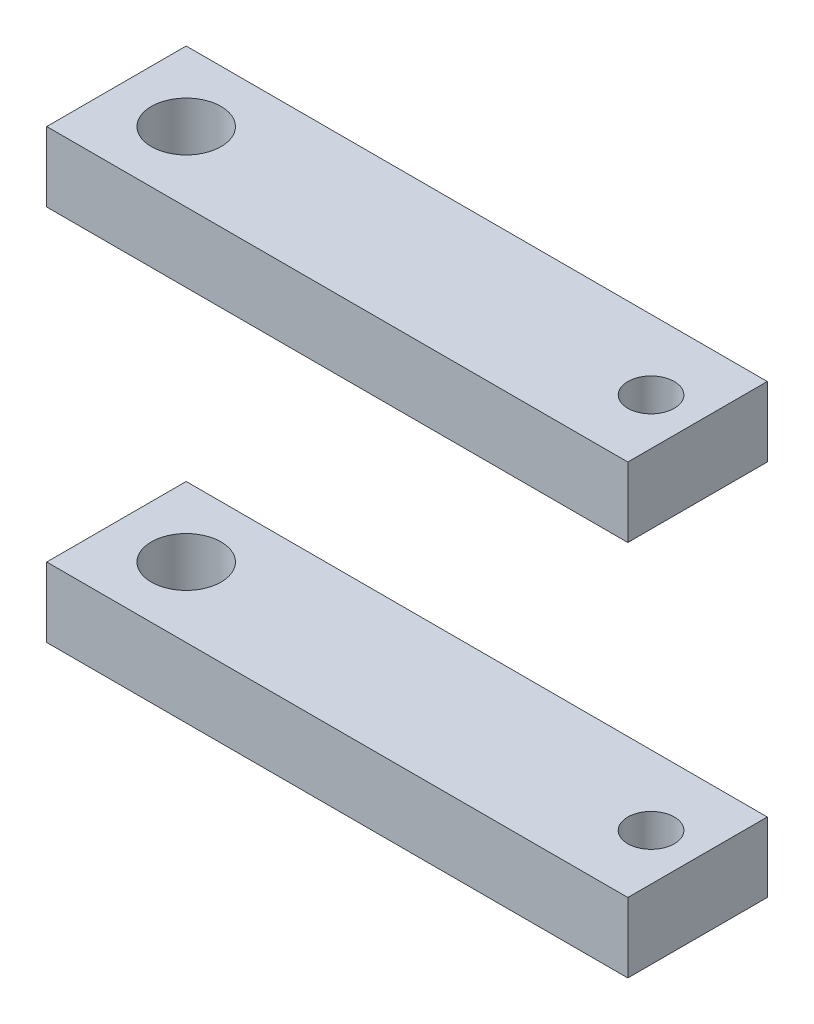
SolidWorks part; units mm, degrees
ref_plane "Ön Düzlem" through (0, 0, 0) normal (0, 0, 1) x (1, 0, 0)
ref_plane "Üst Düzlem" through (0, 0, 0) normal (0, 1, 0) x (1, 0, 0)
ref_plane "Sağ Düzlem" through (0, 0, 0) normal (1, 0, 0) x (0, 0, -1)
sketch "Çizim1" plane through (0, 0, 0) normal (0, 0, 1) x (1, 0, 0)
  line L1 (-12.5276, -4.1892) -> (-62.5276, -4.1892)
  line L2 (-12.5276, -4.1892) -> (-12.5276, -10.1892)
  line L3 (-12.5276, -10.1892) -> (-62.5276, -10.1892)
  line L4 (-62.5276, -4.1892) -> (-62.5276, -10.1892)
  line L5 (-12.5276, -36.6392) -> (-62.5276, -36.6392)
  line L6 (-12.5276, -36.6392) -> (-12.5276, -42.6392)
  line L7 (-12.5276, -42.6392) -> (-62.5276, -42.6392)
  line L8 (-62.5276, -36.6392) -> (-62.5276, -42.6392)
  dimension "D1" = 26.45
  dimension "D2" = 6
  dimension "D3" = 6
  dimension "D4" = 50
  dimension "D5" = 50
extrude "Yükseklik-Ekstrüzyon1" add sketch "Çizim1" along normal blind 12
sketch "Çizim2" plane through (0, -4.1892, 0) normal (0, 1, 0) x (1, 0, 0)
  line L0 (-12.5276, -6) -> (-16.5276, -6) construction
  line L1 (-12.5276, -12) -> (-12.5276, 0) construction
  line L2 (-62.5276, -6) -> (-56.5276, -6) construction
  line L3 (-62.5276, -12) -> (-62.5276, 0) construction
  circle A0 centre (-56.5276, -6) radius 3
  circle A1 centre (-16.5276, -6) radius 2
  dimension "D3" = 6
  dimension "D4" = 4
  dimension "D1" = 6
  dimension "D2" = 4
extrude "Kes-Ekstrüzyon1" cut sketch "Çizim2" against normal blind 40
